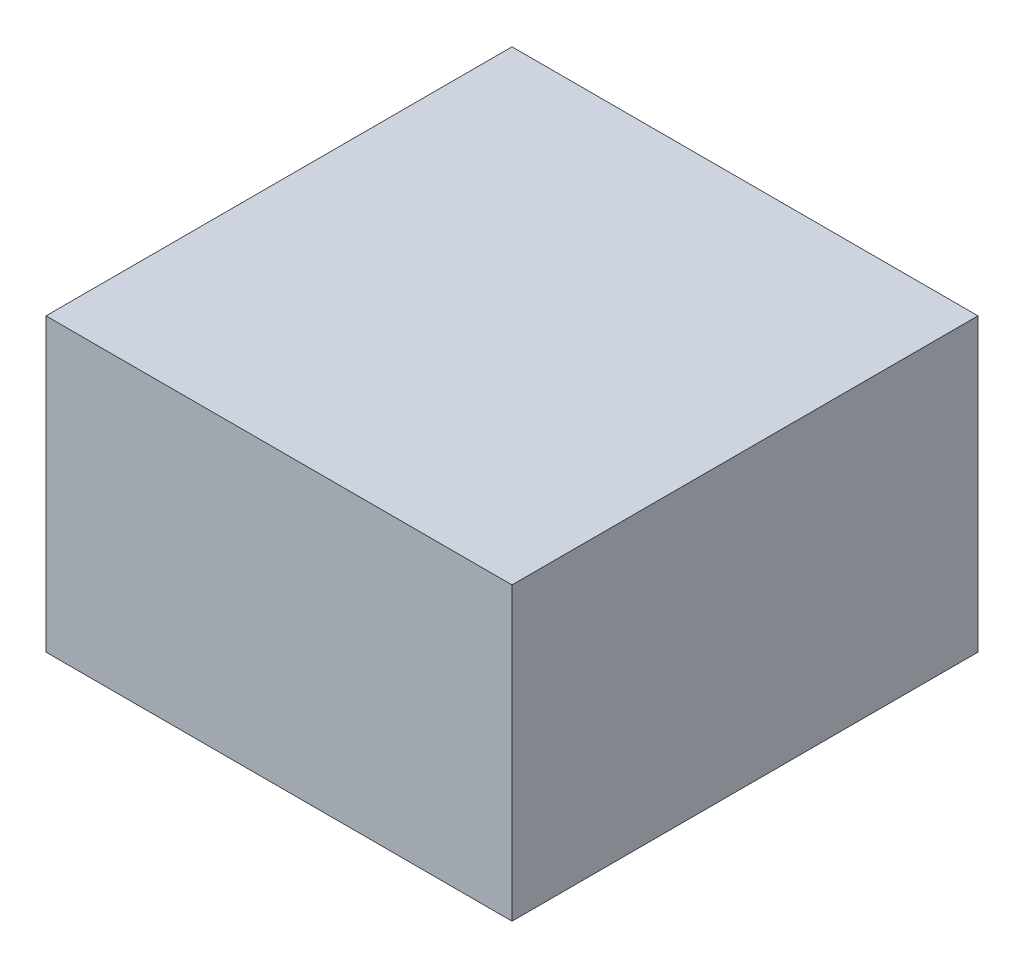
SolidWorks part; units mm, degrees
ref_plane "Front Plane" through (0, 0, 0) normal (0, 0, 1) x (1, 0, 0)
ref_plane "Top Plane" through (0, 0, 0) normal (0, 1, 0) x (1, 0, 0)
ref_plane "Right Plane" through (0, 0, 0) normal (1, 0, 0) x (0, 0, -1)
sketch "Sketch1" plane through (0, 0, 0) normal (0, 1, 0) x (1, 0, 0)
  line L1 (-101.6, 101.6) -> (101.6, 101.6)
  line L2 (-101.6, 101.6) -> (-101.6, -101.6)
  line L3 (-101.6, -101.6) -> (101.6, -101.6)
  line L4 (101.6, 101.6) -> (101.6, -101.6)
  line L5 (-101.6, 101.6) -> (101.6, -101.6) construction
  line L6 (-101.6, -101.6) -> (101.6, 101.6) construction
  point P0 (0, 0)
  dimension "D1" = 203.2
extrude "Boss-Extrude1" add sketch "Sketch1" along normal blind 127
